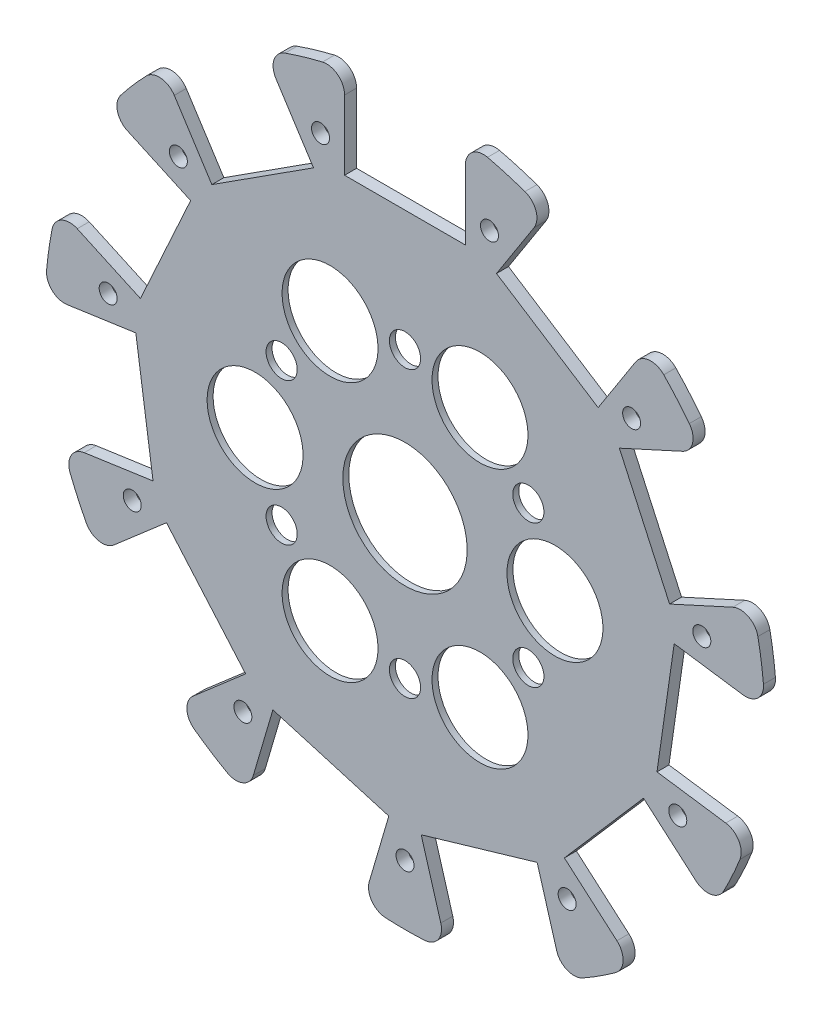
SolidWorks part; units mm, degrees
ref_plane "Front Plane" through (0, 0, 0) normal (0, 0, 1) x (1, 0, 0)
ref_plane "Top Plane" through (0, 0, 0) normal (0, 1, 0) x (1, 0, 0)
ref_plane "Right Plane" through (0, 0, 0) normal (1, 0, 0) x (0, 0, -1)
sketch "Sketch1" plane through (0, 0, 0) normal (0, 0, 1) x (1, 0, 0)
  line L44 (21.5207, 52.1193) -> (15.2567, 42.3722)
  line L47 (-10.0734, 55.4805) -> (-10.0734, 43.8941)
  line L48 (-10.0734, 43.8941) -> (10.0734, 43.8941)
  line L49 (10.0734, 55.4805) -> (10.0734, 43.8941)
  line L51 (38.4693, 41.2271) -> (32.2052, 31.48)
  line L52 (15.2567, 42.3722) -> (32.2052, 31.48)
  line L53 (46.2822, 32.2105) -> (35.7428, 27.3974)
  line L55 (54.6515, 13.8844) -> (44.1121, 9.0712)
  line L56 (35.7428, 27.3974) -> (44.1121, 9.0712)
  line L57 (56.3494, 2.0752) -> (44.8809, 3.7241)
  line L59 (53.4822, -17.8666) -> (42.0137, -16.2176)
  line L60 (44.8809, 3.7241) -> (42.0137, -16.2176)
  line L61 (48.526, -28.719) -> (39.7696, -21.1316)
  line L63 (35.3327, -43.945) -> (26.5763, -36.3575)
  line L64 (39.7696, -21.1316) -> (26.5763, -36.3575)
  line L65 (25.296, -50.3952) -> (22.0318, -39.2781)
  line L67 (5.9653, -56.0712) -> (2.701, -44.9541)
  line L68 (22.0318, -39.2781) -> (2.701, -44.9541)
  line L69 (-5.9653, -56.0712) -> (-2.701, -44.9541)
  line L71 (-25.296, -50.3952) -> (-22.0318, -39.2781)
  line L72 (-2.701, -44.9541) -> (-22.0318, -39.2781)
  line L73 (-35.3327, -43.945) -> (-26.5763, -36.3575)
  line L75 (-48.526, -28.719) -> (-39.7696, -21.1316)
  line L76 (-26.5763, -36.3575) -> (-39.7696, -21.1316)
  line L77 (-53.4822, -17.8666) -> (-42.0137, -16.2176)
  line L79 (-56.3494, 2.0752) -> (-44.8809, 3.7241)
  line L80 (-42.0137, -16.2176) -> (-44.8809, 3.7241)
  line L81 (-54.6515, 13.8844) -> (-44.1121, 9.0712)
  line L83 (-46.2822, 32.2105) -> (-35.7428, 27.3974)
  line L84 (-44.1121, 9.0712) -> (-35.7428, 27.3974)
  line L85 (-38.4693, 41.2271) -> (-32.2052, 31.48)
  line L87 (-21.5207, 52.1193) -> (-15.2567, 42.3722)
  line L88 (-32.2052, 31.48) -> (-15.2567, 42.3722)
  arc A33 (-43.1506, 41.6896) -> (-47.4063, 36.7783) centre (0, 0) ccw
  arc A34 (-13.7615, 58.4005) -> (-19.9968, 56.5697) centre (0, 0) ccw
  arc A35 (19.9968, 56.5697) -> (13.7615, 58.4005) centre (0, 0) ccw
  arc A36 (47.4063, 36.7783) -> (43.1506, 41.6896) centre (0, 0) ccw
  arc A37 (59.7646, 5.3101) -> (58.8397, 11.7426) centre (0, 0) ccw
  arc A38 (53.148, -27.844) -> (55.8476, -21.9327) centre (0, 0) ccw
  arc A39 (29.6574, -52.1578) -> (35.1243, -48.6444) centre (0, 0) ccw
  arc A40 (-3.2493, -59.912) -> (3.2493, -59.912) centre (0, 0) ccw
  arc A41 (-35.1243, -48.6444) -> (-29.6574, -52.1578) centre (0, 0) ccw
  arc A42 (-55.8476, -21.9327) -> (-53.148, -27.844) centre (0, 0) ccw
  arc A43 (-58.8397, 11.7426) -> (-59.7646, 5.3101) centre (0, 0) ccw
  arc A44 (-54.6515, 13.8844) -> (-58.8397, 11.7426) centre (-55.8977, 11.1555) ccw
  arc A45 (-56.3494, 2.0752) -> (-59.7646, 5.3101) centre (-56.7763, 5.0446) cw
  arc A46 (-48.526, -28.719) -> (-53.148, -27.844) centre (-50.4906, -26.4518) cw
  arc A47 (-53.4822, -17.8666) -> (-55.8476, -21.9327) centre (-53.0553, -20.836) ccw
  arc A48 (-25.296, -50.3952) -> (-29.6574, -52.1578) centre (-28.1745, -49.55) cw
  arc A49 (-35.3327, -43.945) -> (-35.1243, -48.6444) centre (-33.3681, -46.2122) ccw
  arc A50 (-5.9653, -56.0712) -> (-3.2493, -59.912) centre (-3.0868, -56.9164) ccw
  arc A51 (5.9653, -56.0712) -> (3.2493, -59.912) centre (3.0868, -56.9164) cw
  arc A52 (35.3327, -43.945) -> (35.1243, -48.6444) centre (33.3681, -46.2122) cw
  arc A53 (25.296, -50.3952) -> (29.6574, -52.1578) centre (28.1745, -49.55) ccw
  arc A54 (48.526, -28.719) -> (53.148, -27.844) centre (50.4906, -26.4518) ccw
  arc A55 (53.4822, -17.8666) -> (55.8476, -21.9327) centre (53.0553, -20.836) cw
  arc A56 (56.3494, 2.0752) -> (59.7646, 5.3101) centre (56.7763, 5.0446) ccw
  arc A57 (54.6515, 13.8844) -> (58.8397, 11.7426) centre (55.8977, 11.1555) cw
  arc A58 (46.2822, 32.2105) -> (47.4063, 36.7783) centre (45.036, 34.9394) ccw
  arc A59 (38.4693, 41.2271) -> (43.1506, 41.6896) centre (40.9931, 39.6052) cw
  arc A60 (21.5207, 52.1193) -> (19.9968, 56.5697) centre (18.997, 53.7412) ccw
  arc A61 (10.0734, 55.4805) -> (13.7615, 58.4005) centre (13.0734, 55.4805) cw
  arc A62 (-10.0734, 55.4805) -> (-13.7615, 58.4005) centre (-13.0734, 55.4805) ccw
  arc A63 (-21.5207, 52.1193) -> (-19.9968, 56.5697) centre (-18.997, 53.7412) cw
  arc A64 (-38.4693, 41.2271) -> (-43.1506, 41.6896) centre (-40.9931, 39.6052) ccw
  arc A65 (-46.2822, 32.2105) -> (-47.4063, 36.7783) centre (-45.036, 34.9394) cw
  point P3 (-57.9879, 15.408)
  point P51 (0, 0)
  point P55 (-57.1127, -18.3885)
  point P60 (-38.1047, -46.3469)
  point P63 (-6.9987, -59.5904)
  point P70 (26.3294, -53.9144)
  point P73 (51.298, -31.121)
  point P78 (59.9799, 1.5532)
  point P83 (49.6186, 33.7342)
  point P88 (23.5037, 55.2048)
  point P93 (-10.0734, 59.1483)
  dimension "D1" = 120
  dimension "D2" = 3
extrude "Boss-Extrude1" add sketch "Sketch1" along normal blind 2
sketch "Sketch4" plane through (0, 0, 2) normal (0, 0, 1) x (1, 0, 0)
  line L0 (0, 17.7708) -> (0, 0) construction
  line L1 (0, 0) -> (-14.0866, 47.9746) construction
  circle A0 centre (-14.0866, 47.9746) radius 1.5
  circle A1 centre (14.0866, 47.9746) radius 1.5
  circle A2 centre (37.7875, 32.743) radius 1.5
  circle A3 centre (49.4911, 7.1157) radius 1.5
  circle A4 centre (45.4816, -20.7708) radius 1.5
  circle A5 centre (27.032, -42.0627) radius 1.5
  circle A6 centre (0, -50) radius 1.5
  circle A7 centre (-27.032, -42.0627) radius 1.5
  circle A8 centre (-45.4816, -20.7708) radius 1.5
  circle A9 centre (-49.4911, 7.1157) radius 1.5
  circle A10 centre (-37.7875, 32.743) radius 1.5
  point P28 (0, 0)
  dimension "D1" = 3
  dimension "D2" = 50
  dimension "D3" = 16.364
extrude "Cut-Extrude3" cut sketch "Sketch4" against normal blind 2
sketch "Sketch6" plane through (0, 0, 0) normal (0, 0, -1) x (-1, 0, 0)
  circle A0 centre (0, 0) radius 35
  dimension "D1" = 70
extrude "Cut-Extrude4" cut sketch "Sketch6" against normal blind 1
sketch "Sketch7" plane through (0, 0, 1) normal (0, 0, -1) x (-1, 0, 0)
  line L0 (0, 13.8429) -> (0, 0) construction
  line L1 (0, 0) -> (-12.5, 21.6506) construction
  circle A0 centre (0, 0) radius 10.3658
  circle A1 centre (0, 23.75) radius 2.6
  circle A2 centre (-12.5, 21.6506) radius 8
  circle A3 centre (20.5681, 11.875) radius 2.6
  circle A4 centre (12.5, 21.6506) radius 8
  circle A5 centre (20.5681, -11.875) radius 2.6
  circle A6 centre (25, 0) radius 8
  circle A7 centre (0, -23.75) radius 2.6
  circle A8 centre (12.5, -21.6506) radius 8
  circle A9 centre (-20.5681, -11.875) radius 2.6
  circle A10 centre (-12.5, -21.6506) radius 8
  circle A11 centre (-20.5681, 11.875) radius 2.6
  circle A12 centre (-25, 0) radius 8
  point P30 (0, 0)
  dimension "D1" = 5.2
  dimension "D5" = 16
  dimension "D2" = 23.75
  dimension "D3" = 25
  dimension "D4" = 30
  dimension "D6" = 6
extrude "Cut-Extrude5" cut sketch "Sketch7" against normal blind 1
